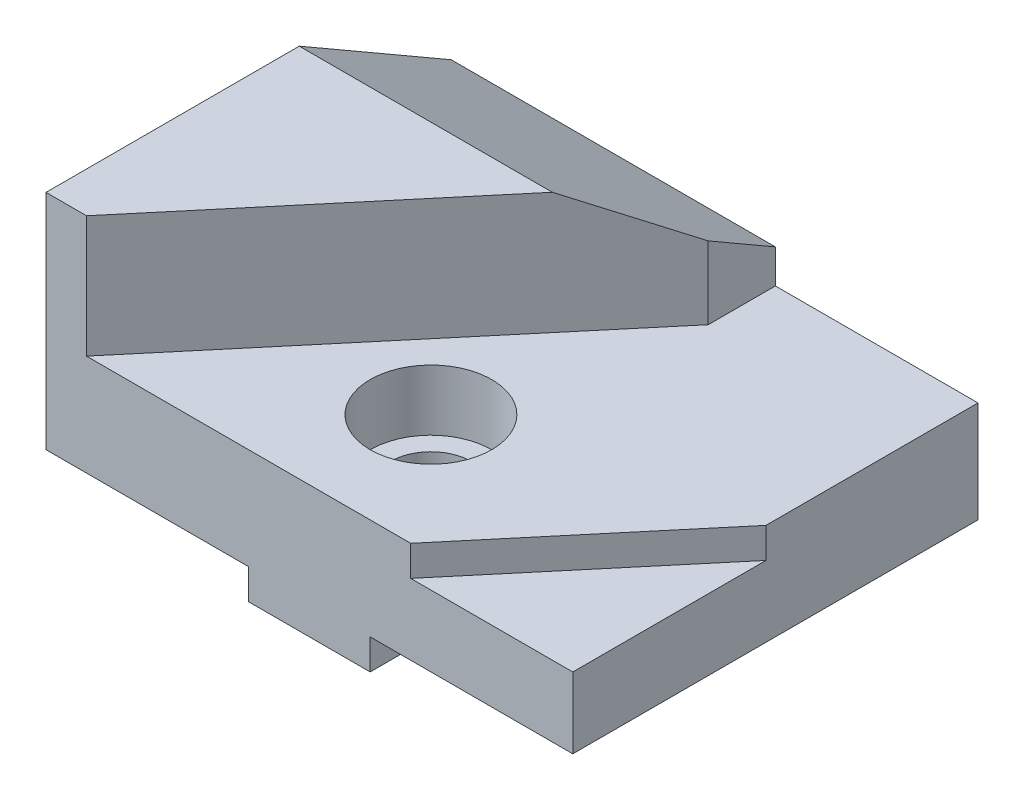
SolidWorks part; units mm, degrees
material "Nickel"
ref_plane "Plan de face" through (0, 0, 0) normal (0, 0, 1) x (1, 0, 0)
ref_plane "Plan de dessus" through (0, 0, 0) normal (0, 1, 0) x (1, 0, 0)
ref_plane "Plan de droite" through (0, 0, 0) normal (1, 0, 0) x (0, 0, -1)
sketch "Esquisse4" plane through (0, 0, 0) normal (0, 0, 1) x (1, 0, 0)
  line L1 (-9.525, 0) -> (9.525, 0)
  line L2 (-41.275, 4.7625) -> (-41.275, 39.6875)
  line L3 (-41.275, 39.6875) -> (41.275, 39.6875)
  line L4 (41.275, 4.7625) -> (41.275, 39.6875)
  line L7 (-41.275, 4.7625) -> (-9.525, 4.7625)
  line L8 (-9.525, 0) -> (-9.525, 4.7625)
  line L11 (41.275, 4.7625) -> (9.525, 4.7625)
  line L12 (9.525, 0) -> (9.525, 4.7625)
  point P0 (0, 0)
  point P3 (-9.525, 8.3332)
  point P10 (9.525, 22.0091)
  point P12 (9.525, 24.7197)
  dimension "D1" = 82.55
  dimension "D2" = 19.05
  dimension "D3" = 39.6875
  dimension "D4" = 4.7625
  dimension "D5" = 31.75
extrude "Boss.-Extru.2" add sketch "Esquisse4" against normal blind 63.5
sketch "Esquisse5" plane through (0, 39.6875, 0) normal (0, 1, 0) x (1, 0, 0)
  line L0 (-34.925, 0) -> (9.525, 52.9734)
  line L1 (41.275, 0) -> (-41.275, 0) construction
  line L2 (9.525, 52.9734) -> (9.525, 63.5)
  line L3 (41.275, 63.5) -> (-41.275, 63.5) construction
  dimension "D1" = 6.35
  dimension "D2" = 31.75
  dimension "D3" = 50
extrude "Enlèv. mat.-Extru.2" cut sketch "Esquisse5" against normal blind 19.05 and the other way through all flip side to cut
chamfer "Chanfrein2" distance 23.8125 angle 30 1 edges at (-15.875, 39.6875, -63.5)
sketch "Esquisse6" plane through (0, 20.6375, 0) normal (0, 1, 0) x (1, 0, 0)
  line L0 (15.875, 0) -> (41.275, 30.2705)
  line L1 (41.275, 0) -> (-34.925, 0) construction
  line L2 (41.275, 63.5) -> (41.275, 0) construction
  line L3 (41.275, 30.2705) -> (41.275, 0)
  line L4 (41.275, 0) -> (15.875, 0)
  line L5 (-34.925, 0) -> (9.525, 52.9734) construction
  dimension "D1" = 25.4
extrude "Enlèv. mat.-Extru.3" cut sketch "Esquisse6" against normal blind 4.7625
hole_wizard "Chambrage pour vis à tête ronde bombée 1/21" positions "Esquisse7" profile "Esquisse8" counterbore size "1/2" standard "Ansi Inch" end condition through all
sketch "Esquisse7" plane through (0, 20.6375, 0) normal (0, 1, 0) x (1, 0, 0)
  line L0 (15.875, 0) -> (-34.925, 0) construction
  point P0 (0, 19.05)
  point P5 (0, 0)
  dimension "D1" = 19.05
sketch "Esquisse8" plane through (0, 20.6375, -19.05) normal (1, 0, 0) x (0, 0, 1)
  line L0 (0, 0) -> (0, 20.6375)
  line L1 (0, 20.6375) -> (6.35, 20.6375)
  line L3 (6.35, 20.6375) -> (6.35, 9.525)
  line L4 (6.35, 9.525) -> (9.525, 9.525)
  line L5 (9.525, 9.525) -> (9.525, 0)
  line L7 (9.525, 0) -> (0, 0)
  line L11 (0, -6.35) -> (0, 107.95) construction
  dimension "Diamètre du perçage jusqu'au prochain" = 12.7
  dimension "Profondeur du perçage jusqu'au prochain" = 20.6375
  dimension "Diamètre du chambrage" = 19.05
  dimension "Profondeur du chambrage" = 9.525
